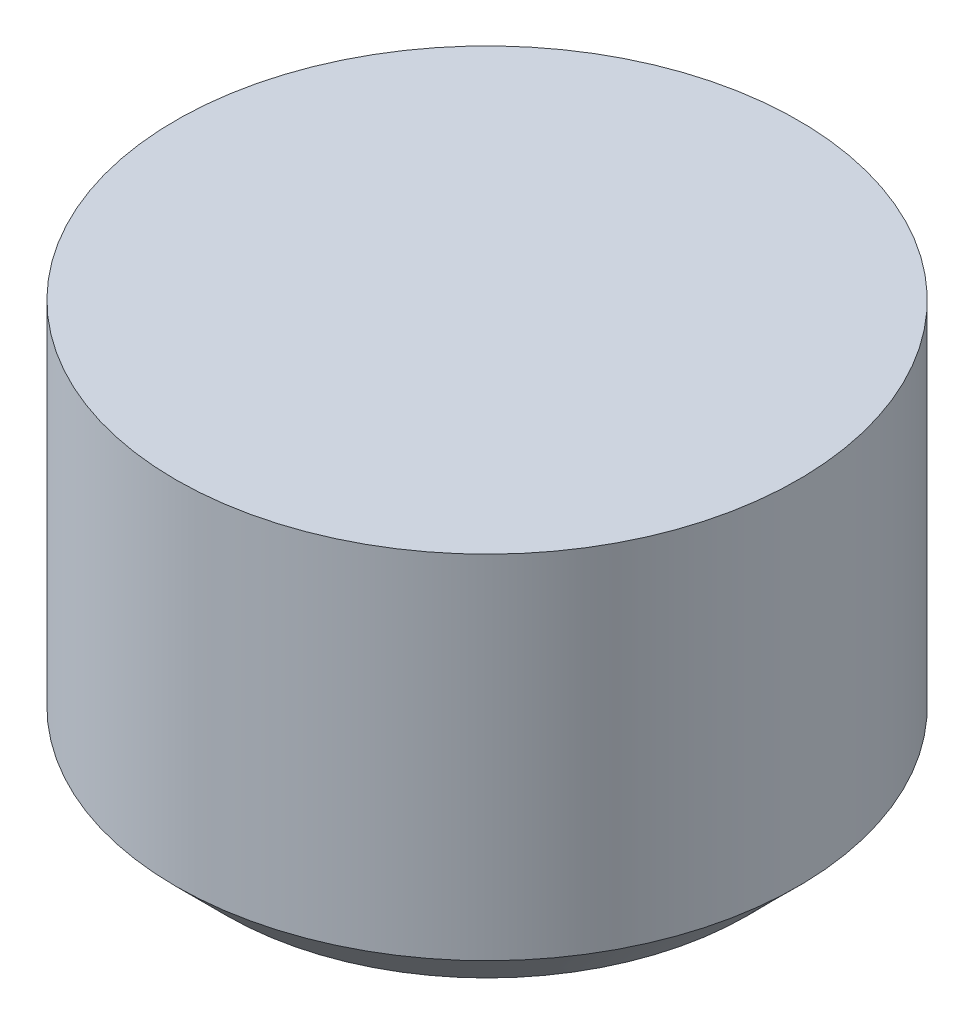
SolidWorks part; units mm, degrees
ref_plane "前视基准面" through (0, 0, 0) normal (0, 0, 1) x (1, 0, 0)
ref_plane "上视基准面" through (0, 0, 0) normal (0, 1, 0) x (1, 0, 0)
ref_plane "右视基准面" through (0, 0, 0) normal (1, 0, 0) x (0, 0, -1)
sketch "草图1" plane through (0, 0, 0) normal (0, 1, 0) x (1, 0, 0)
  circle A0 centre (0, 0) radius 12.2
  dimension "D1" = 24.4
extrude "凸台-拉伸1" add sketch "草图1" along normal blind 15.8
chamfer "倒角1" distance 2 angle 45 1 edges at (0, 0, 12.2)
sketch "草图2" plane through (0, 0, 0) normal (0, -1, 0) x (1, 0, 0)
  circle A0 centre (0, 0) radius 3
  dimension "D1" = 6
extrude "凸台-拉伸2" add sketch "草图2" along normal blind 4
